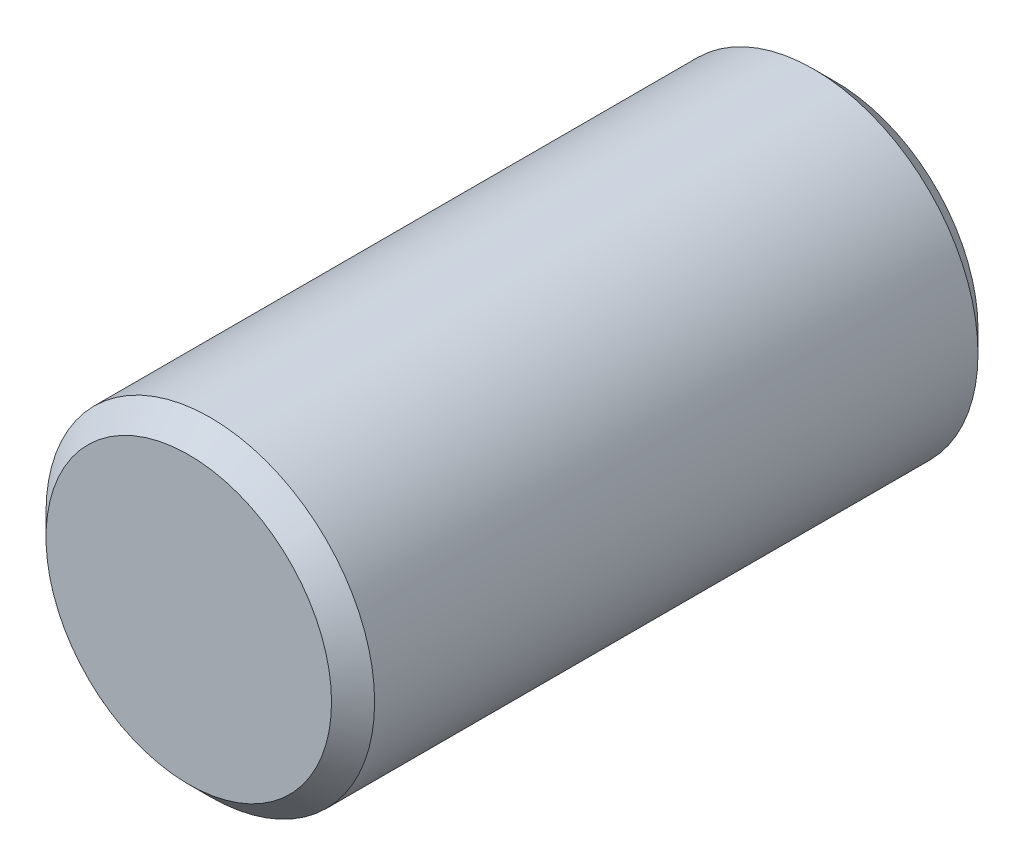
SolidWorks part; units mm, degrees
ref_plane "前视基准面" through (0, 0, 0) normal (0, 0, 1) x (1, 0, 0)
ref_plane "上视基准面" through (0, 0, 0) normal (0, 1, 0) x (1, 0, 0)
ref_plane "右视基准面" through (0, 0, 0) normal (1, 0, 0) x (0, 0, -1)
other "Configuration Table"
sketch "草图1" plane through (0, 0, 0) normal (0, 0, 1) x (1, 0, 0)
  circle A0 centre (0, 0) radius 1.525
  dimension "D1" = 3.05
extrude "凸台-拉伸1" add sketch "草图1" along normal blind 6
chamfer "倒角1" distance 0.2 angle 45 2 edges at (1.525, 0, 6) (1.525, 0, 0)
